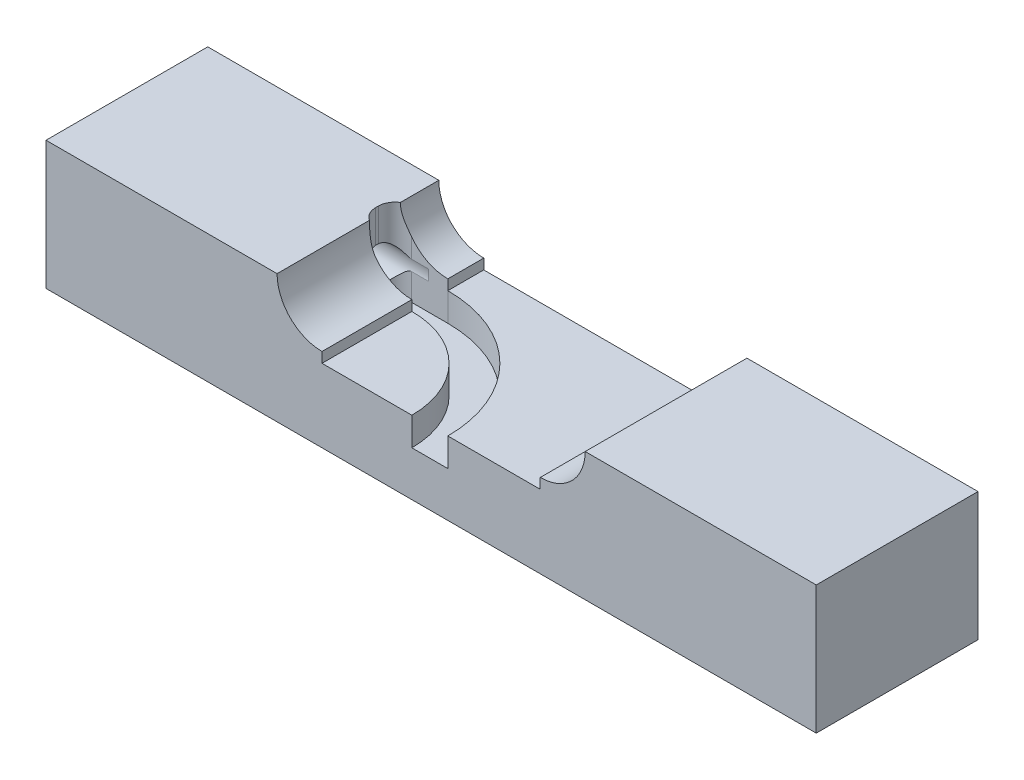
SolidWorks part; units mm, degrees
ref_plane "Front Plane" through (0, 0, 0) normal (0, 0, 1) x (1, 0, 0)
ref_plane "Top Plane" through (0, 0, 0) normal (0, 1, 0) x (1, 0, 0)
ref_plane "Right Plane" through (0, 0, 0) normal (1, 0, 0) x (0, 0, -1)
sketch "Sketch1" plane through (0, 0, 0) normal (0, 1, 0) x (1, 0, 0)
  line L1 (-19.05, -4.0005) -> (19.05, -4.0005)
  line L2 (-19.05, -4.0005) -> (-19.05, 4.0005)
  line L3 (-19.05, 4.0005) -> (19.05, 4.0005)
  line L4 (19.05, -4.0005) -> (19.05, 4.0005)
  line L5 (-19.05, -4.0005) -> (19.05, 4.0005) construction
  line L6 (-19.05, 4.0005) -> (19.05, -4.0005) construction
  point P0 (0, 0)
  dimension "D1" = 38.1
  dimension "D2" = 8.001
extrude "Boss-Extrude1" add sketch "Sketch1" along normal blind 6.35
sketch "Sketch2" plane through (0, 0, -4.0005) normal (0, 0, -1) x (-1, 0, 0)
  line L0 (5.3975, 6.35) -> (-5.3975, 6.35) construction
  line L1 (5.3975, 4.1275) -> (-5.3975, 4.1275)
  line L2 (5.3975, 8.5725) -> (-5.3975, 8.5725)
  line L3 (19.05, 6.35) -> (-19.05, 6.35) construction
  line L4 (-19.05, 0) -> (19.05, 0) construction
  line L6 (19.05, 6.35) -> (19.05, 0) construction
  line L7 (-19.05, 6.35) -> (-19.05, 0) construction
  arc A0 (5.3975, 4.1275) -> (5.3975, 8.5725) centre (5.3975, 6.35) ccw
  arc A1 (-5.3975, 8.5725) -> (-5.3975, 4.1275) centre (-5.3975, 6.35) ccw
  point P2 (0, 6.35)
  dimension "D1" = 6.35
  dimension "D2" = 10.795
  dimension "D3" = 4.445
extrude "Cut-Extrude1" cut sketch "Sketch2" against normal blind 25.4
ref_plane "Plane1" through (0, 4.1275, 0) normal (0, 1, 0) x (1, 0, 0)
sketch "Sketch4" plane through (0, 4.1275, 0) normal (0, 1, 0) x (1, 0, 0)
  line L1 (0.8255, -4.0005) -> (-0.9525, -4.0005)
  line L2 (-5.3975, 0.4445) -> (-7.1855, 0.4445)
  line L3 (-8.011, 1.27) -> (-8.011, 1.397)
  line L4 (-7.1855, 2.2225) -> (-5.3975, 2.2225)
  arc A0 (-0.9525, -4.0005) -> (-5.3975, 0.4445) centre (-5.3975, -4.0005) ccw
  arc A1 (0.8255, -4.0005) -> (-5.3975, 2.2225) centre (-5.3975, -4.0005) ccw
  arc A2 (-8.011, 1.27) -> (-7.1855, 0.4445) centre (-7.1855, 1.27) ccw
  arc A3 (-7.1855, 2.2225) -> (-8.011, 1.397) centre (-7.1855, 1.397) ccw
  dimension "D1" = 8.89
  dimension "D2" = 12.446
  dimension "D3" = 2.6135
  dimension "D4" = 1.778
  dimension "D5" = 0.8255
extrude "Cut-Extrude2" cut sketch "Sketch4" against normal blind 1.905 and the other way through all
ref_plane "Plane3" through (-19.05, 0, 0) normal (-1, 0, 0) x (0, 0, 1)
sketch "Sketch5" plane through (19.05, 0, 0) normal (1, 0, 0) x (0, 0, -1)
  line L0 (-4.0005, 6.35) -> (-4.0005, 0) construction
  line L1 (-4.0005, 6.35) -> (4.0005, 6.35) construction
  circle A0 centre (1.3335, 3.81) radius 0.9271
  dimension "D2" = 1.8542
  dimension "D1" = 5.334
  dimension "D3" = 2.54
extrude "Cut-Extrude3" cut sketch "Sketch5" along normal blind 12.7 from surface at -38.1 starting at plane "Plane3"
fillet "Fillet3" [suppressed] radius 6.35
sketch "Sketch6" plane through (0, 4.1275, 0) normal (0, 1, 0) x (1, 0, 0)
  line L1 (5.3975, -4.0005) -> (-5.3975, -4.0005)
  line L2 (5.3975, -4.0005) -> (5.3975, 4.0005)
  line L3 (5.3975, 4.0005) -> (-5.3975, 4.0005)
  line L4 (-5.3975, -4.0005) -> (-5.3975, 4.0005)
extrude "Cut-Extrude4" cut sketch "Sketch6" against normal blind 0.508
